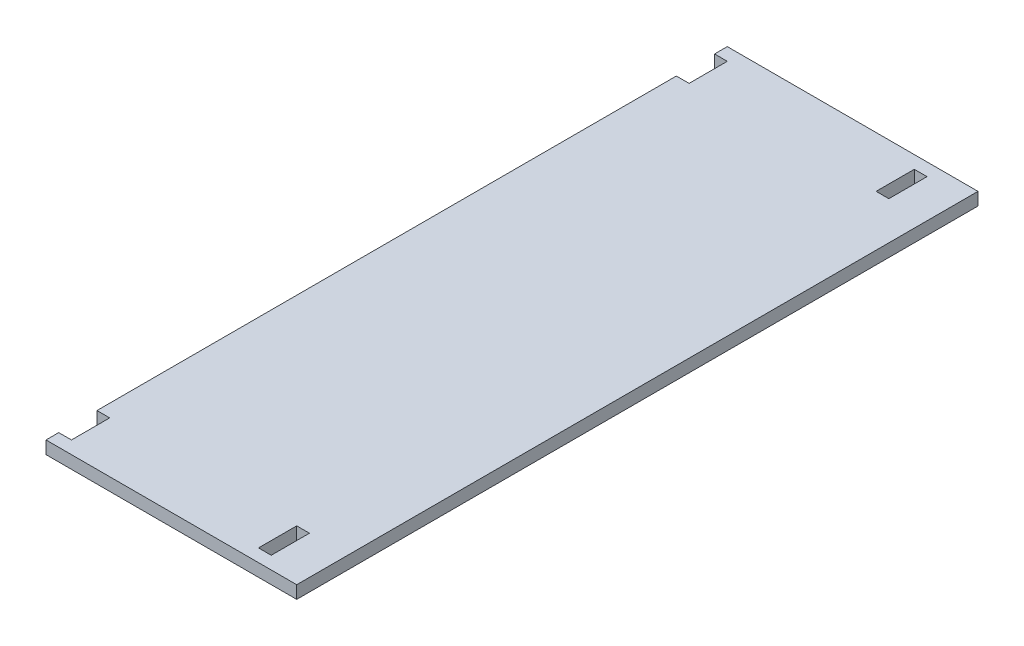
SolidWorks part; units mm, degrees
ref_plane "Front Plane" through (0, 0, 0) normal (0, 0, 1) x (1, 0, 0)
ref_plane "Top Plane" through (0, 0, 0) normal (0, 1, 0) x (1, 0, 0)
ref_plane "Right Plane" through (0, 0, 0) normal (1, 0, 0) x (0, 0, -1)
sketch "Sketch1" plane through (0, 0, 0) normal (0, 1, 0) x (1, 0, 0)
  line L0 (-31.242, 72.1995) -> (-28.067, 72.1995)
  line L1 (-31.242, 84.8995) -> (31.242, 84.8995)
  line L2 (-31.242, 84.8995) -> (-31.242, 81.7245)
  line L3 (-31.242, -84.8995) -> (31.242, -84.8995)
  line L4 (31.242, 84.8995) -> (31.242, -84.8995)
  line L5 (-28.067, 72.1995) -> (-28.067, 81.7245)
  line L6 (18.542, 81.7245) -> (18.542, 72.1995)
  line L7 (18.542, 72.1995) -> (21.717, 72.1995)
  line L8 (21.717, 72.1995) -> (21.717, 81.7245)
  line L9 (-31.242, -72.1995) -> (-28.067, -72.1995)
  line L10 (-28.067, -72.1995) -> (-28.067, -81.7245)
  line L11 (18.542, -81.7245) -> (18.542, -72.1995)
  line L12 (18.542, -72.1995) -> (21.717, -72.1995)
  line L13 (21.717, -72.1995) -> (21.717, -81.7245)
  line L14 (-31.242, 81.7245) -> (-28.067, 81.7245)
  line L15 (18.542, 81.7245) -> (21.717, 81.7245)
  line L16 (-31.242, -81.7245) -> (-28.067, -81.7245)
  line L17 (18.542, -81.7245) -> (21.717, -81.7245)
  line L18 (-31.242, 72.1995) -> (-31.242, -72.1995)
  line L19 (-31.242, -81.7245) -> (-31.242, -84.8995)
  point P4 (0, 84.8995)
  dimension "D1" = 169.799
  dimension "D2" = 62.484
  dimension "D3" = 3.175
  dimension "D4" = 3.175
  dimension "D5" = 3.175
  dimension "D6" = 3.175
  dimension "D11" = 52.959
  dimension "D12" = 9.525
  dimension "D13" = 9.525
  dimension "D14" = 9.525
extrude "Boss-Extrude1" add sketch "Sketch1" along normal blind 3.175
